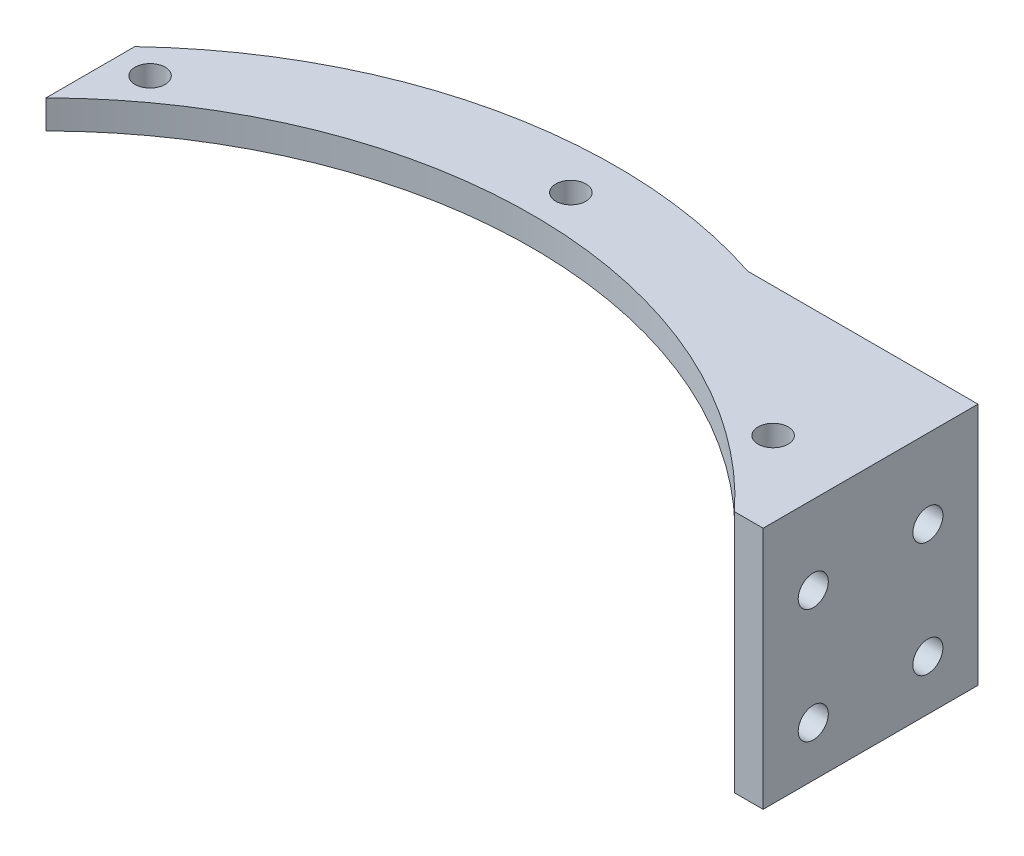
SolidWorks part; units mm, degrees
ref_plane "Front" through (0, 0, 0) normal (0, 0, 1) x (1, 0, 0)
ref_plane "Top" through (0, 0, 0) normal (0, 1, 0) x (1, 0, 0)
ref_plane "Right" through (0, 0, 0) normal (1, 0, 0) x (0, 0, -1)
sketch "Sketch1" plane through (0, 0, 0) normal (0, 1, 0) x (1, 0, 0)
  line L6 (19.1852, -38.1257) -> (19.1852, -50.5222)
  line L7 (67.2772, -98.9898) -> (67.2772, 49901.0102) construction
  line L8 (117.2772, -52.4931) -> (117.2772, -22.4931)
  line L9 (117.2772, -22.4931) -> (89.1447, -22.4931)
  arc A0 (19.1852, -50.5222) -> (117.2772, -52.4931) centre (67.2772, -98.9898) cw
  arc A1 (19.1852, -38.1257) -> (89.1447, -22.4931) centre (67.2772, -88.9898) cw
  circle A2 centre (67.2772, -25.3367) radius 2.1
  circle A3 centre (23.7843, -40.5902) radius 2.1
  circle A4 centre (110.7702, -40.5902) radius 2.1
extrude "Boss-Extrude1" add sketch "Sketch1" along normal blind 4
sketch "Sketch3" plane through (117.2772, 0, 0) normal (1, 0, 0) x (0, 0, -1)
  line L1 (-52.4931, 4) -> (-22.4931, 4)
  line L2 (-52.4931, 4) -> (-52.4931, -30)
  line L3 (-52.4931, -30) -> (-22.4931, -30)
  line L4 (-22.4931, 4) -> (-22.4931, -30)
  point P4 (-23.4763, 4)
extrude "Boss-Extrude4" add sketch "Sketch3" along normal blind 4
sketch "Sketch4" plane through (117.2772, 0, 0) normal (-1, 0, 0) x (0, 0, 1)
  circle A1 centre (29.4922, -6.9991) radius 2.1
  circle A2 centre (45.494, -6.9991) radius 2.1
  circle A3 centre (45.494, -23.0009) radius 2.1
  circle A4 centre (29.4922, -23.0009) radius 2.1
  dimension "D1" = 4
extrude "Cut-Extrude1" cut sketch "Sketch4" against normal blind 4
